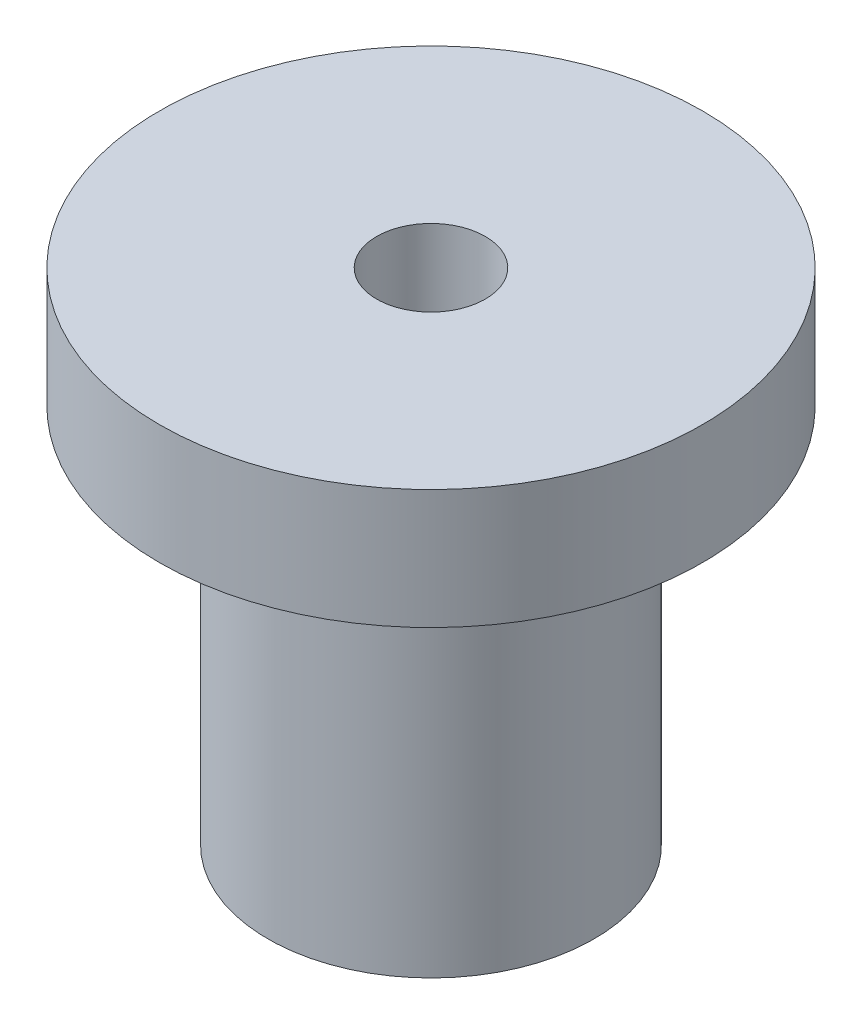
SolidWorks part; units mm, degrees
ref_plane "Front Plane" through (0, 0, 0) normal (0, 0, 1) x (1, 0, 0)
ref_plane "Top Plane" through (0, 0, 0) normal (0, 1, 0) x (1, 0, 0)
ref_plane "Right Plane" through (0, 0, 0) normal (1, 0, 0) x (0, 0, -1)
sketch "Sketch1" plane through (0, 0, 0) normal (0, 0, 1) x (1, 0, 0)
  line L0 (25, 0) -> (75, 0)
  line L1 (75, 0) -> (75, 175)
  line L2 (75, 175) -> (125, 175)
  line L3 (125, 175) -> (125, 230)
  line L4 (125, 230) -> (25, 230)
  line L5 (25, 230) -> (25, 0)
  line L6 (0, 0) -> (0, 277.5137) construction
  point P0 (25, 0)
  dimension "D1" = 25
  dimension "D2" = 175
  dimension "D3" = 50
  dimension "D4" = 55
  dimension "D5" = 100
revolve "Revolve1" add sketch "Sketch1" angle 360 about L6
